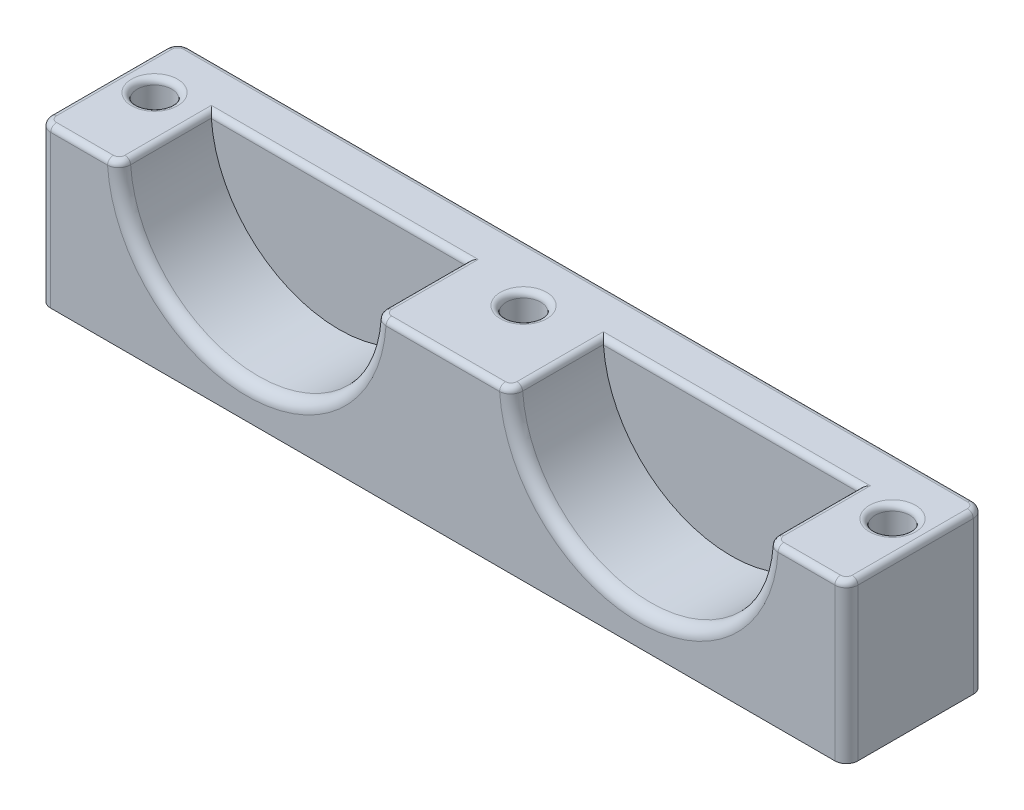
SolidWorks part; units mm, degrees
ref_plane "Front" through (0, 0, 0) normal (0, 0, 1) x (1, 0, 0)
ref_plane "Top" through (0, 0, 0) normal (0, 1, 0) x (1, 0, 0)
ref_plane "Right" through (0, 0, 0) normal (1, 0, 0) x (0, 0, -1)
sketch "Sketch1" plane through (0, 0, 0) normal (0, 0, 1) x (1, 0, 0)
  line L1 (35, -7) -> (-35, -7)
  line L2 (35, -7) -> (35, 7)
  line L3 (35, 7) -> (-35, 7)
  line L4 (-35, -7) -> (-35, 7)
  line L5 (35, -7) -> (-35, 7) construction
  line L6 (35, 7) -> (-35, -7) construction
  point P0 (0, 0)
  dimension "D1" = 14
  dimension "D2" = 70
extrude "Boss-Extrude1" add sketch "Sketch1" along normal blind 12
sketch "Sketch2" plane through (0, 0, 12) normal (0, 0, 1) x (1, 0, 0)
  line L0 (35, 7) -> (-35, 7) construction
  line L1 (0, 0) -> (0, 15.6255)
  circle A0 centre (17, 7) radius 11.1
  line M4 (35, 7) -> (-35, 7)
  dimension "D1" = 22.2
  dimension "D2" = 17
extrude "Cut-Extrude1" cut sketch "Sketch2" against normal blind 8 contours A0 M4 | A0 M4
mirror "Mirror1" about plane through (0, 0, 0) normal (1, 0, 0) of "Cut-Extrude1"
sketch "Sketch3" plane through (0, 7, 0) normal (0, 1, 0) x (1, 0, 0)
  line L0 (-35, -12) -> (-35, 0) construction
  line L1 (-28.1, -12) -> (-35, -12) construction
  circle A0 centre (-32, -5) radius 1.5
  circle A1 centre (0, -5) radius 1.5
  circle A2 centre (32, -5) radius 1.5
  dimension "D1" = 3
  dimension "D2" = 3
  dimension "D3" = 7
  dimension "D4" = 3
extrude "Cut-Extrude2" cut sketch "Sketch3" against normal through all
sketch "Sketch4" plane through (-35, 0, 0) normal (-1, 0, 0) x (0, 0, 1)
  line L0 (12, 7) -> (12, -7) construction
  line L1 (0, 7) -> (12, 7)
  line L2 (0, 7) -> (0, 6.7)
  line L3 (0, 6.7) -> (12, 6.7)
  line L4 (12, 7) -> (12, 6.7)
  dimension "D1" = 0.3
extrude "Cut-Extrude3" cut sketch "Sketch4" against normal through all
fillet "Fillet1" radius 1 6 edges at (35, -0.15, 0) (35, -0.15, 12) (17, -4.1, 12) (-17, -4.1, 12) (-35, -0.15, 0) (-35, -0.15, 12)
fillet "Fillet2" radius 0.5 23 edges at (34.7071, 6.7, 11.7071) (31.5481, 6.7, 12) (5.5288, 6.7, 11.7807) (28.315, 6.7, 11.6245) (5.9041, 6.7, 7.5) (28.0959, 6.7, 7.5) (17, 6.7, 4) (0, 6.7, 12) (-28.4712, 6.7, 11.7807) (-5.685, 6.7, 11.6245) (-28.0959, 6.7, 7.5) (-5.9041, 6.7, 7.5) (-17, 6.7, 4) (-31.5481, 6.7, 12) (-34.7071, 6.7, 11.7071) (-35, 6.7, 6) (-34.7071, 6.7, 0.2929) (0, 6.7, 0) (34.7071, 6.7, 0.2929) (35, 6.7, 6) (0, 6.7, 3.5) (32, 6.7, 3.5) (-32, 6.7, 3.5)
